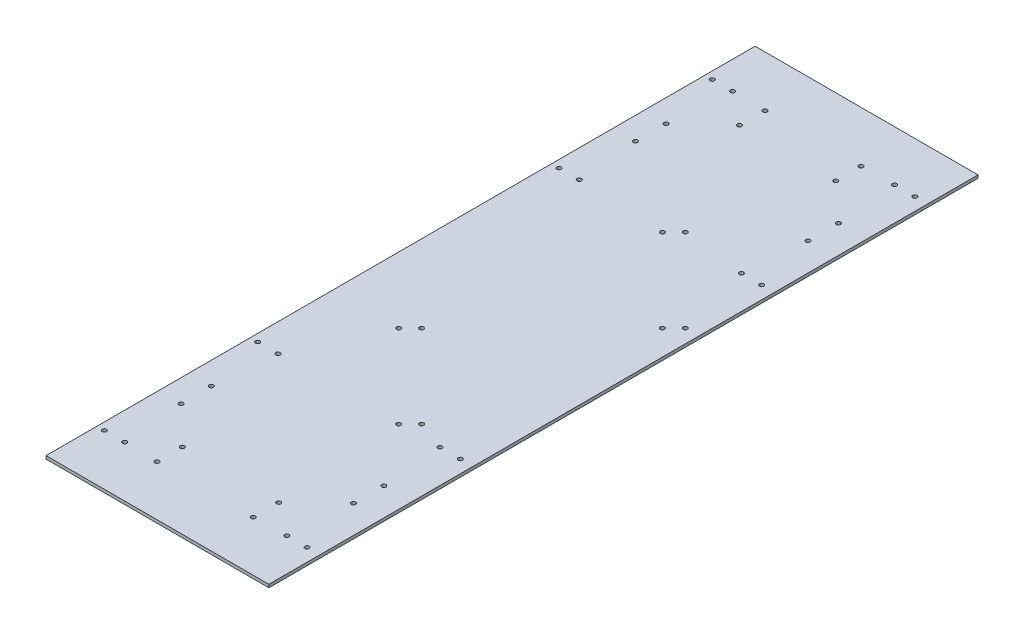
SolidWorks part; units mm, degrees
ref_plane "Front Plane" through (0, 0, 0) normal (0, 0, 1) x (1, 0, 0)
ref_plane "Top Plane" through (0, 0, 0) normal (0, 1, 0) x (1, 0, 0)
ref_plane "Right Plane" through (0, 0, 0) normal (1, 0, 0) x (0, 0, -1)
sketch "Sketch1" plane through (0, 0, 0) normal (0, 1, 0) x (1, 0, 0)
  line L1 (-110, 350) -> (110, 350)
  line L2 (-110, 350) -> (-110, -350)
  line L3 (-110, -350) -> (110, -350)
  line L4 (110, 350) -> (110, -350)
  dimension "D1" = 220
  dimension "D2" = 700
  dimension "D3" = 350
  dimension "D4" = 110
extrude "Boss-Extrude1" add sketch "Sketch1" along normal blind 3
sketch "Sketch2" plane through (0, 3, 0) normal (0, 1, 0) x (1, 0, 0)
  circle A0 centre (44.9391, 299.6686) radius 2.125
  circle A1 centre (44.9391, 274.6686) radius 2.125
  circle A2 centre (-50.0609, 274.6686) radius 2.125
  circle A3 centre (-50.0609, 299.6686) radius 2.125
  circle A4 centre (-50.0609, -300.3314) radius 2.125
  circle A5 centre (-50.0609, -275.3314) radius 2.125
  circle A6 centre (44.9391, -275.3314) radius 2.125
  circle A7 centre (44.9391, -300.3314) radius 2.125
extrude "Cut-Extrude1" cut sketch "Sketch2" against normal blind 3
sketch "Sketch3" plane through (0, 3, 0) normal (0, 1, 0) x (1, 0, 0)
  circle A0 centre (77.3486, 300.3314) radius 2.125
  circle A1 centre (77.3486, 149.0614) radius 2.125
  circle A2 centre (82.4586, 239.6964) radius 2.125
  circle A3 centre (82.4586, 209.6964) radius 2.125
  circle A4 centre (97.3486, 149.0614) radius 2.125
  circle A5 centre (97.3486, 300.3314) radius 2.125
  circle A6 centre (-102.6514, 300.3314) radius 2.125
  circle A7 centre (-102.6514, 149.0614) radius 2.125
  circle A8 centre (-87.7614, 209.6964) radius 2.125
  circle A9 centre (-87.7614, 239.6964) radius 2.125
  circle A10 centre (-82.6514, 149.0614) radius 2.125
  circle A11 centre (-82.6514, 300.3314) radius 2.125
  circle A12 centre (-82.6514, -299.6686) radius 2.125
  circle A13 centre (-82.6514, -148.3986) radius 2.125
  circle A14 centre (-87.7614, -239.0336) radius 2.125
  circle A15 centre (-87.7614, -209.0336) radius 2.125
  circle A16 centre (-102.6514, -148.3986) radius 2.125
  circle A17 centre (-102.6514, -299.6686) radius 2.125
  circle A18 centre (97.3486, -299.6686) radius 2.125
  circle A19 centre (97.3486, -148.3986) radius 2.125
  circle A20 centre (82.4586, -209.0336) radius 2.125
  circle A21 centre (82.4586, -239.0336) radius 2.125
  circle A22 centre (77.3486, -148.3986) radius 2.125
  circle A23 centre (77.3486, -299.6686) radius 2.125
extrude "Cut-Extrude2" cut sketch "Sketch3" against normal blind 3
sketch "Sketch4" plane through (0, 3, 0) normal (0, 1, 0) x (1, 0, 0)
  line L0 (-261.4013, 290.9958) -> (65.8547, -36.2602) construction
  line L1 (-183.5666, 71.7398) -> (175.8547, -287.6815) construction
  line L2 (-160.9392, 71.7398) -> (175.8547, -265.0541) construction
  line L3 (-178.6011, 78.088) -> (180.6865, -281.1996) construction
  circle A0 centre (119.1806, -231.0074) radius 2.125
  circle A1 centre (-126.8925, 15.0657) radius 2.125
  circle A2 centre (37.1562, -148.983) radius 2.125
  circle A3 centre (-44.8682, -66.9587) radius 2.125
  circle A4 centre (130.4943, -219.6937) radius 2.125
  circle A5 centre (48.4699, -137.6693) radius 2.125
  circle A6 centre (-33.5545, -55.6449) radius 2.125
  circle A7 centre (-115.5788, 26.3794) radius 2.125
  circle A8 centre (3.2151, 145.1734) radius 2.125
  circle A9 centre (85.2395, 63.149) radius 2.125
  circle A10 centre (167.2639, -18.8754) radius 2.125
  circle A11 centre (249.2883, -100.8998) radius 2.125
  circle A12 centre (96.5532, 74.4627) radius 2.125
  circle A13 centre (178.5776, -7.5617) radius 2.125
  circle A14 centre (14.5288, 156.4871) radius 2.125
  circle A15 centre (260.602, -89.5861) radius 2.125
  point P15 (-3.856, -107.9708)
  point P41 (137.5654, 33.4505)
  dimension "D2" = 4.25
  dimension "D4" = 4.25
  dimension "D7" = 4.25
  dimension "D9" = 4.25
  dimension "D1" = 100
  dimension "D3" = 16
  dimension "D5" = 348
  dimension "D6" = 174
  dimension "D8" = 116
  dimension "D10" = 116
  dimension "D11" = 8
extrude "Cut-Extrude3" cut sketch "Sketch4" against normal blind 3
